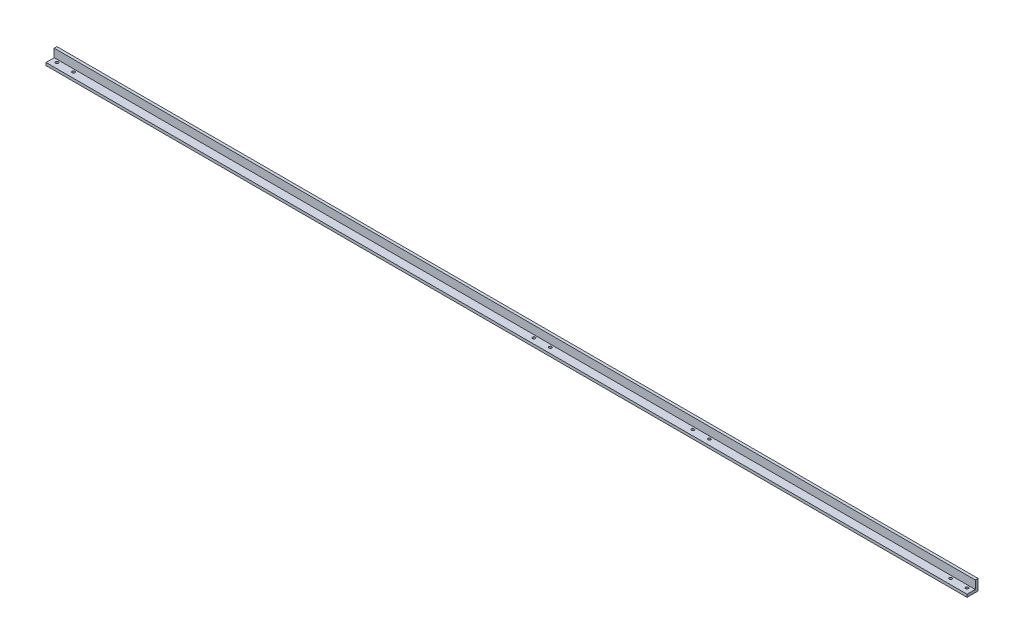
SolidWorks part; units mm, degrees
material "6061-T6 (SS)"
ref_plane "Front Plane" through (0, 0, 0) normal (0, 0, 1) x (1, 0, 0)
ref_plane "Top Plane" through (0, 0, 0) normal (0, 1, 0) x (1, 0, 0)
ref_plane "Right Plane" through (0, 0, 0) normal (1, 0, 0) x (0, 0, -1)
sketch "Sketch1" plane through (0, 0, 0) normal (1, 0, 0) x (0, 0, -1)
  line L0 (0, 0) -> (0, 19.05)
  line L1 (0, 19.05) -> (6.35, 19.05)
  line L2 (6.35, 19.05) -> (6.35, -6.35)
  line L3 (6.35, -6.35) -> (-19.05, -6.35)
  line L4 (-19.05, -6.35) -> (-19.05, 0)
  line L5 (-19.05, 0) -> (0, 0)
  point P8 (0, 0)
  dimension "D1" = 25.4
  dimension "D2" = 25.4
  dimension "D3" = 6.35
  dimension "D4" = 6.35
extrude "Boss-Extrude1" add sketch "Sketch1" along normal blind 2133.6
sketch "Sketch2" plane through (0, -6.35, 0) normal (0, -1, 0) x (1, 0, 0)
  line L0 (0, 6.35) -> (2133.6, 6.35) construction
  line L1 (0, 19.05) -> (0, -6.35) construction
  line L2 (1168.4, -6.35) -> (1168.4, 19.05) construction
  line L3 (2133.6, -6.35) -> (0, -6.35) construction
  line L4 (2133.6, 19.05) -> (0, 19.05) construction
  line L5 (2133.6, 19.05) -> (2133.6, -6.35) construction
  line L6 (1473.2, -6.35) -> (1473.2, 19.05) construction
  circle A0 centre (12.7, 6.35) radius 3.175
  circle A1 centre (50.8, 6.35) radius 3.175
  circle A2 centre (1117.6, 6.35) radius 3.175
  circle A3 centre (1155.7, 6.35) radius 3.175
  circle A4 centre (1485.9, 6.35) radius 3.175
  circle A5 centre (1524, 6.35) radius 3.175
  circle A6 centre (2082.8, 6.35) radius 3.175
  circle A7 centre (2120.9, 6.35) radius 3.175
  dimension "D1" = 6.35
  dimension "D2" = 6.35
  dimension "D3" = 12.7
  dimension "D4" = 50.8
  dimension "D6" = 6.35
  dimension "D7" = 12.7
  dimension "D8" = 50.8
  dimension "D11" = 6.35
  dimension "D12" = 12.7
  dimension "D13" = 50.8
  dimension "D14" = 12.7
  dimension "D15" = 6.35
  dimension "D5" = 1168.4
  dimension "D9" = 660.4
  dimension "D10" = 304.8
  dimension "D16" = 50.8
extrude "Cut-Extrude1" cut sketch "Sketch2" against normal blind 914.4
